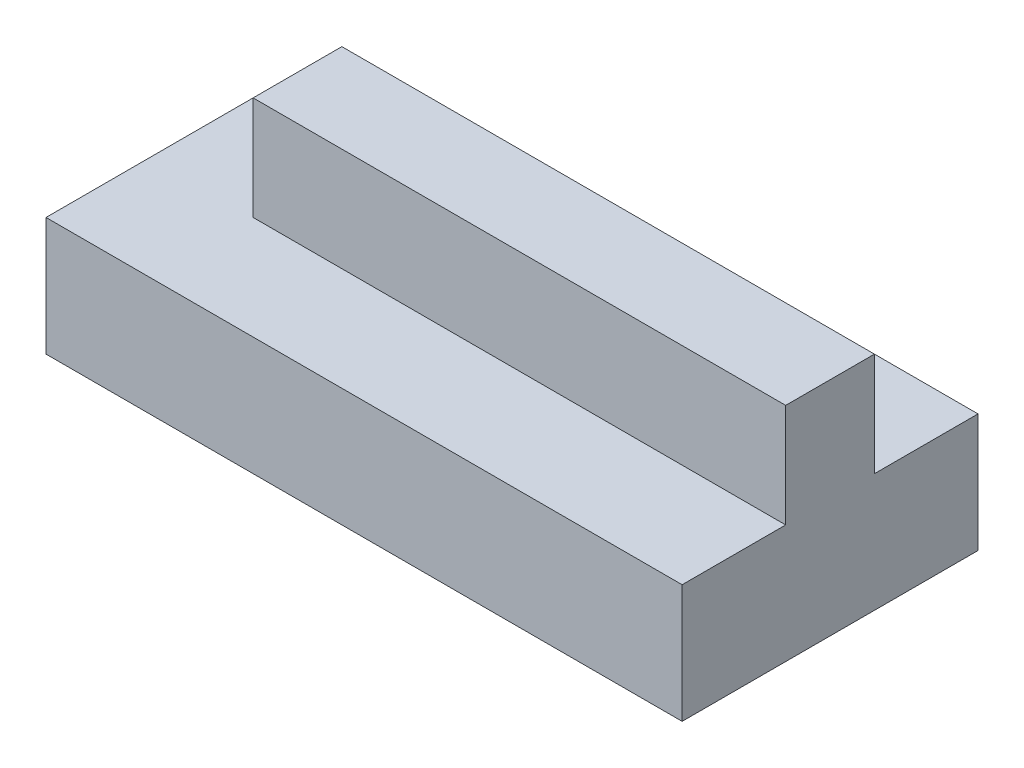
SolidWorks part; units mm, degrees
ref_plane "Front Plane" through (0, 0, 0) normal (0, 0, 1) x (1, 0, 0)
ref_plane "Top Plane" through (0, 0, 0) normal (0, 1, 0) x (1, 0, 0)
ref_plane "Right Plane" through (0, 0, 0) normal (1, 0, 0) x (0, 0, -1)
sketch "Sketch1" plane through (0, 0, 0) normal (0, 1, 0) x (1, 0, 0)
  line L1 (0, 0) -> (21.5, 0)
  line L2 (0, 0) -> (0, 10)
  line L3 (0, 10) -> (21.5, 10)
  line L4 (21.5, 0) -> (21.5, 10)
  dimension "D1" = 10
  dimension "D2" = 21.5
extrude "Boss-Extrude1" add sketch "Sketch1" along normal blind 4
sketch "Sketch2" plane through (0, 4, 0) normal (0, 1, 0) x (1, 0, 0)
  line L0 (3.5, 3.5) -> (0, 3.5) construction
  line L1 (3.5, 3.5) -> (21.5, 3.5)
  line L2 (3.5, 3.5) -> (3.5, 6.5)
  line L3 (3.5, 6.5) -> (21.5, 6.5)
  line L4 (21.5, 3.5) -> (21.5, 6.5)
  line L5 (0, 10) -> (0, 0) construction
  line L6 (3.5, 3.5) -> (3.5, 0) construction
  line L7 (0, 0) -> (21.5, 0) construction
  line L8 (3.5, 6.5) -> (3.5, 10) construction
  line L9 (21.5, 10) -> (0, 10) construction
  line L10 (3.5, 6.5) -> (0, 6.5) construction
  line L11 (21.5, 0) -> (21.5, 10) construction
  dimension "D1" = 3.5
extrude "Boss-Extrude2" add sketch "Sketch2" along normal blind 3.5
